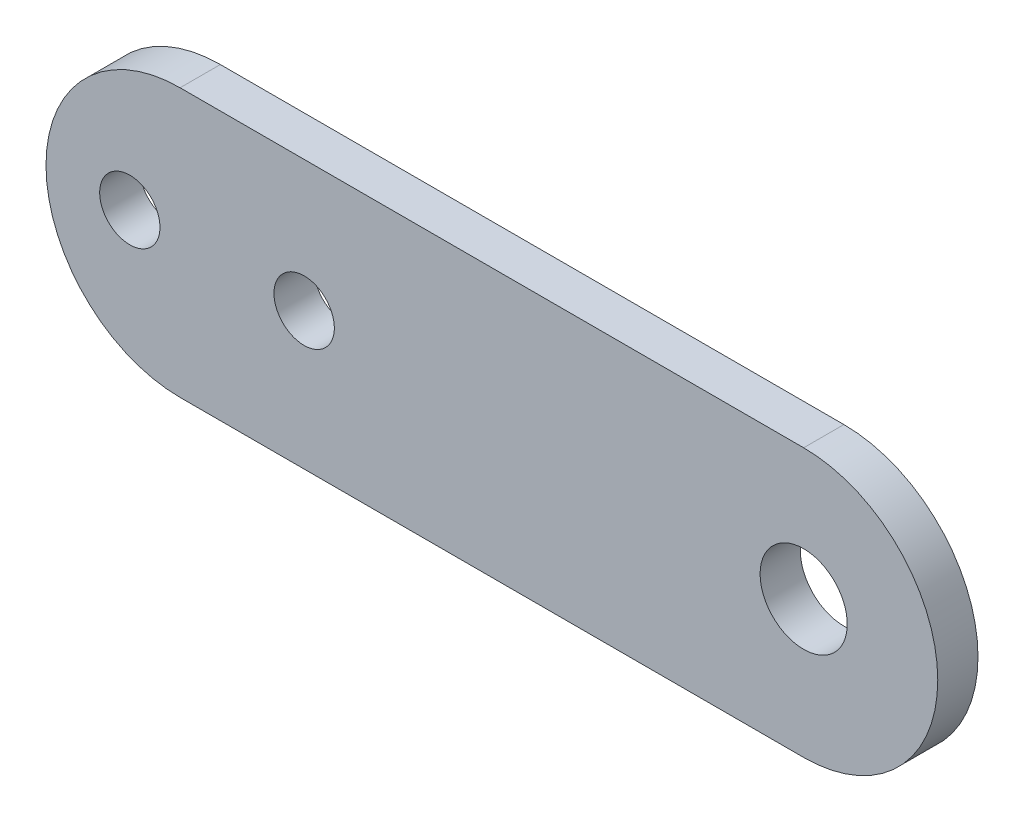
SolidWorks part; units mm, degrees
material "6063-T5"
ref_plane "Alzado" through (0, 0, 0) normal (0, 0, 1) x (1, 0, 0)
ref_plane "Planta" through (0, 0, 0) normal (0, 1, 0) x (1, 0, 0)
ref_plane "Vista lateral" through (0, 0, 0) normal (1, 0, 0) x (0, 0, -1)
sketch "Croquis1" plane through (0, 0, 0) normal (0, 0, 1) x (1, 0, 0)
  line L0 (-36.2236, -0.2314) -> (39.2258, -0.2314) construction
  line L1 (-23.25, 9.7686) -> (23.25, 9.7686)
  line L3 (-23.25, -10.2314) -> (23.25, -10.2314)
  line L5 (0, 17.4588) -> (0, -17.7464) construction
  arc A0 (23.25, -10.2314) -> (23.25, 9.7686) centre (23.25, -0.2314) ccw
  arc A1 (-23.25, 9.7686) -> (-23.25, -10.2314) centre (-23.25, -0.2314) ccw
  point P13 (0, 0)
  dimension "D2" = 46.5
  dimension "D1" = 20
extrude "Saliente-Extruir1" add sketch "Croquis1" along normal blind 3
sketch "Croquis2" plane through (0, 0, 0) normal (0, 0, -1) x (-1, 0, 0)
  line L0 (33.25, -0.2314) -> (33.25, 14.4502) construction
  line L1 (-33.25, -0.2314) -> (-33.25, 16.271) construction
  circle A0 centre (14, 0) radius 2.25
  circle A1 centre (27, 0) radius 2.25
  arc A3 (23.25, -10.2314) -> (23.25, 9.7686) centre (23.25, -0.2314) ccw construction
  circle A4 centre (-23.25, 0) radius 3.25
  arc A5 (-23.25, 9.7686) -> (-23.25, -10.2314) centre (-23.25, -0.2314) ccw construction
  point P0 (14, 0)
  point P1 (27, 0)
  dimension "D2" = 6.25
  dimension "D3" = 4.5
  dimension "D4" = 6.5
  dimension "D1" = 13
  dimension "D5" = 10
extrude "Cortar-Extruir1" cut sketch "Croquis2" against normal blind 3
